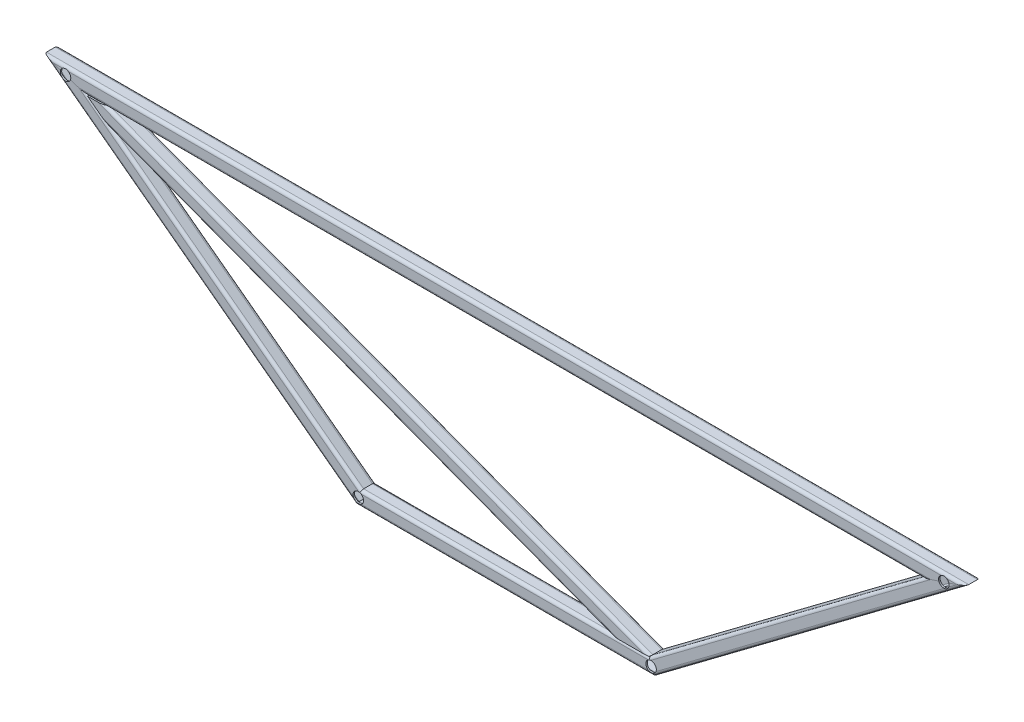
SolidWorks part; units mm, degrees
ref_plane "Front Plane" through (0, 0, 0) normal (0, 0, 1) x (1, 0, 0)
ref_plane "Top Plane" through (0, 0, 0) normal (0, 1, 0) x (1, 0, 0)
ref_plane "Right Plane" through (0, 0, 0) normal (1, 0, 0) x (0, 0, -1)
sketch "Sketch3" plane through (0, 0, 0) normal (0, 0, 1) x (1, 0, 0)
  line L0 (600, 0) -> (-600, 0)
  line L1 (-600, 0) -> (-200, -300)
  line L2 (-200, -300) -> (200, -300)
  line L3 (200, -300) -> (600, 0)
  line L4 (-600, 0) -> (200, -300)
  point P4 (0, 0)
  dimension "D1" = 1200
  dimension "D2" = 400
  dimension "D3" = 500
other "Square tube 20 X 20 X 2(2)"
ref_plane "Plane1" through (600, 0, 0) normal (-1, 0, 0) x (0, -1, 0)
sketch "Sketch15" plane through (600, 0, 0) normal (-1, 0, 0) x (0, -1, 0)
  line L0 (-6, -8) -> (6, -8)
  line L1 (-8, -6) -> (-8, 6)
  line L2 (6, 8) -> (-6, 8)
  line L3 (8, 6) -> (8, -6)
  line L4 (-6, -10) -> (6, -10)
  line L5 (-10, -6) -> (-10, 6)
  line L6 (6, 10) -> (-6, 10)
  line L7 (10, 6) -> (10, -6)
  arc A0 (10, 6) -> (6, 10) centre (6, 6) ccw
  arc A1 (6, -10) -> (10, -6) centre (6, -6) ccw
  arc A2 (-10, -6) -> (-6, -10) centre (-6, -6) ccw
  arc A3 (-6, 10) -> (-10, 6) centre (-6, 6) ccw
  arc A4 (-6, 8) -> (-8, 6) centre (-6, 6) ccw
  arc A5 (8, 6) -> (6, 8) centre (6, 6) ccw
  arc A6 (6, -8) -> (8, -6) centre (6, -6) ccw
  arc A7 (-8, -6) -> (-6, -8) centre (-6, -6) ccw
  point P0 (-10, 0)
  point P1 (10, 0)
  point P2 (0, 10)
  point P3 (0, -10)
  point P4 (0, 0)
  point P5 (-10, -10)
  point P6 (10, -10)
  point P7 (10, 10)
  point P8 (-10, 10)
  point P33 (0, 0)
  dimension "D1" = 4
  dimension "Thickness" = 2
  dimension "V_leg" = 20
other "Square tube 20 X 20 X 2(1)"
ref_plane "Plane2" through (-600, 0, 0) normal (0.9363, -0.3511, 0) x (0.3511, 0.9363, 0)
sketch "Sketch16" plane through (-600, 0, 0) normal (0.9363, -0.3511, 0) x (0.3511, 0.9363, 0)
  line L0 (-6, -8) -> (6, -8)
  line L1 (-8, -6) -> (-8, 6)
  line L2 (6, 8) -> (-6, 8)
  line L3 (8, 6) -> (8, -6)
  line L4 (-6, -10) -> (6, -10)
  line L5 (-10, -6) -> (-10, 6)
  line L6 (6, 10) -> (-6, 10)
  line L7 (10, 6) -> (10, -6)
  arc A0 (10, 6) -> (6, 10) centre (6, 6) ccw
  arc A1 (6, -10) -> (10, -6) centre (6, -6) ccw
  arc A2 (-10, -6) -> (-6, -10) centre (-6, -6) ccw
  arc A3 (-6, 10) -> (-10, 6) centre (-6, 6) ccw
  arc A4 (-6, 8) -> (-8, 6) centre (-6, 6) ccw
  arc A5 (8, 6) -> (6, 8) centre (6, 6) ccw
  arc A6 (6, -8) -> (8, -6) centre (6, -6) ccw
  arc A7 (-8, -6) -> (-6, -8) centre (-6, -6) ccw
  point P0 (-10, 0)
  point P1 (10, 0)
  point P2 (0, 10)
  point P3 (0, -10)
  point P4 (0, 0)
  point P5 (-10, -10)
  point P6 (10, -10)
  point P7 (10, 10)
  point P8 (-10, 10)
  point P33 (0, 0)
  dimension "D1" = 4
  dimension "Thickness" = 2
  dimension "V_leg" = 20
other "Trim/Extend1"
sketch "Sketch18" plane through (0, 0, 10) normal (0, 0, 1) x (1, 0, 0)
  circle A0 centre (-600, 0) radius 7.19
  circle A1 centre (-200, -300) radius 7.19
  circle A2 centre (200, -300) radius 7.19
  circle A3 centre (600, 0) radius 7.19
  dimension "D1" = 14.38
  dimension "D2" = 14.38
  dimension "D3" = 14.38
  dimension "D4" = 14.38
extrude "Cut-Extrude2" cut sketch "Sketch18" against normal through all
